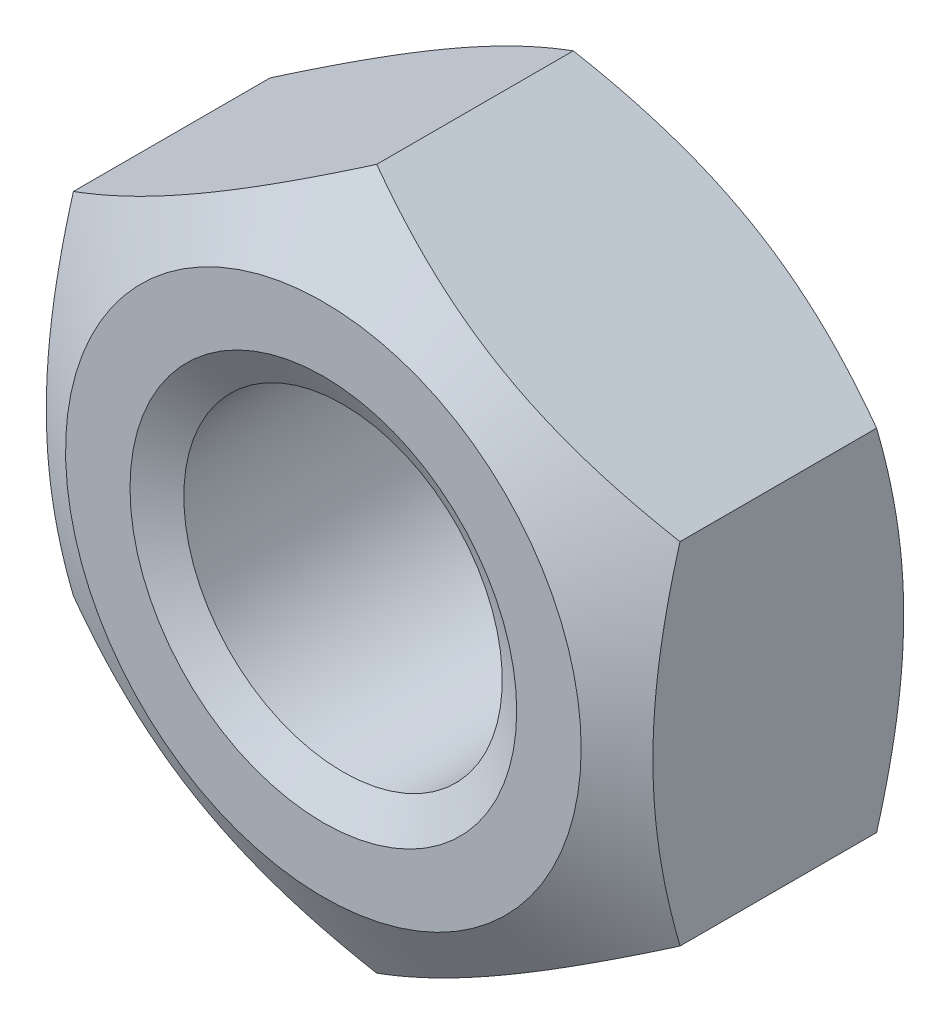
SolidWorks part; units mm, degrees
ref_plane "Front Plane" through (0, 0, 0) normal (0, 0, 1) x (1, 0, 0)
ref_plane "Top Plane" through (0, 0, 0) normal (0, 1, 0) x (1, 0, 0)
ref_plane "Right Plane" through (0, 0, 0) normal (1, 0, 0) x (0, 0, -1)
sketch "Sketch1" plane through (0, 0, 0) normal (0, 0, 1) x (1, 0, 0)
  line L0 (0, 0) -> (0, 4.6188) construction
  line L1 (0, 4.6188) -> (-4, 2.3094)
  line L2 (-4, 2.3094) -> (-4, -2.3094)
  line L3 (-4, -2.3094) -> (0, -4.6188)
  line L4 (0, -4.6188) -> (4, -2.3094)
  line L5 (4, -2.3094) -> (4, 2.3094)
  line L6 (4, 2.3094) -> (0, 4.6188)
  circle A0 centre (0, 0) radius 4 construction
  dimension "S DIM" = 8
extrude "Boss-Extrude1" add sketch "Sketch1" against normal blind 4
sketch "Sketch4" plane through (0, 0, 0) normal (1, 0, 0) x (0, 0, -1)
  line L0 (4, 4.6188) -> (3.2963, 4.6188)
  line L1 (4, 4.6188) -> (0, 4.6188) construction
  line L2 (3.2963, 4.6188) -> (4, 3.4)
  line L4 (4, 3.4) -> (4, 4.6188)
  line L5 (0, 0) -> (3.2979, 0) construction
  line L6 (0, 4.6188) -> (0.7037, 4.6188)
  line L7 (0.7037, 4.6188) -> (0, 3.4)
  line L9 (0, 3.4) -> (0, 4.6188)
  dimension "SAME S 1" = 6.8
  dimension "D2" = 30
  dimension "SAME S 2" = 6.8
  dimension "D4" = 30
revolve "Cut-Revolve1" cut sketch "Sketch4" angle 360 about L5
sketch "Sketch5" plane through (0, 0, 0) normal (1, 0, 0) x (0, 0, -1)
  line L0 (0, 0) -> (4, 0) construction
  line L1 (0, 0) -> (0, 2.55)
  line L2 (0, 3.4) -> (0, -3.4) construction
  line L3 (0, 2.55) -> (0.2598, 2.1)
  line L4 (0.2598, 2.1) -> (3.7402, 2.1)
  line L5 (3.7402, 2.1) -> (4, 2.55)
  line L6 (4, 2.55) -> (4, 0)
  line L8 (4, -3.4) -> (4, 3.4) construction
  line L9 (4, 0) -> (0, 0)
  dimension "D1" = 60
  dimension "D2" = 60
  dimension "Hole2" = 5.1
  dimension "Hole1" = 4.2
revolve "Cut-Revolve2" cut sketch "Sketch5" angle 360 about L0
cosmetic thread "Cosmetic Thread1" parameters "D2"=5
